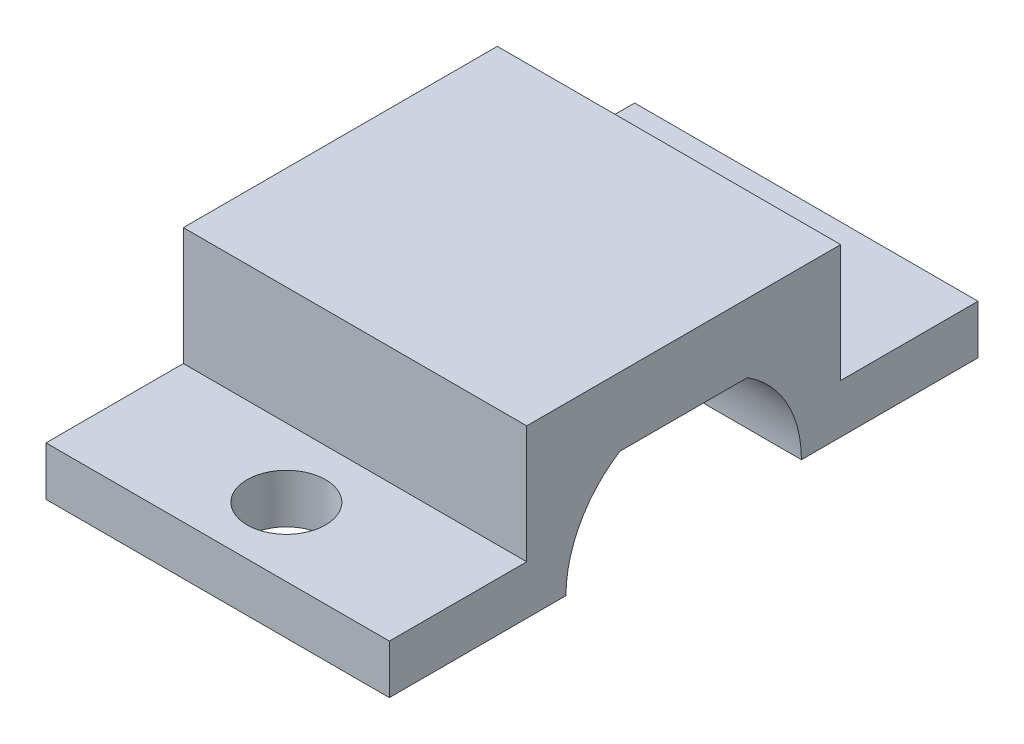
SolidWorks part; units mm, degrees
ref_plane "前基準面" through (0, 0, 0) normal (0, 0, 1) x (1, 0, 0)
ref_plane "上基準面" through (0, 0, 0) normal (0, 1, 0) x (1, 0, 0)
ref_plane "右基準面" through (0, 0, 0) normal (1, 0, 0) x (0, 0, -1)
sketch "草圖1" plane through (0, 0, 0) normal (1, 0, 0) x (0, 0, -1)
  line L0 (-3.25, 2.1203) -> (3.25, 2.1203)
  line L1 (-15, -2.8797) -> (-5.9998, -2.8797)
  line L2 (-15, -2.8797) -> (-15, -0.3829)
  line L3 (-8, 5.6171) -> (8, 5.6171)
  line L4 (15, -2.8797) -> (15, -0.3829)
  line L5 (6.0007, -2.8797) -> (15, -2.8797)
  line L6 (0, -1000) -> (0, 49000) construction
  line L7 (-15, -0.3829) -> (-8, -0.3829)
  line L8 (-8, -0.3829) -> (-8, 5.6171)
  line L13 (15, -0.3829) -> (8, -0.3829)
  line L14 (8, -0.3829) -> (8, 5.6171)
  arc A0 (-5.9998, -2.8797) -> (-3.25, 2.1203) centre (-0.0798, -2.8793) cw
  arc A1 (6.0007, -2.8797) -> (3.25, 2.1203) centre (0.0802, -2.8801) ccw
  dimension "D4" = 5.92
  dimension "D7" = 5.9205
  dimension "D1" = 5
  dimension "D2" = 6.5
  dimension "D3" = 0.16
  dimension "D5" = 7
  dimension "D6" = 6
extrude "填料-伸長1" add sketch "草圖1" along normal mid plane 17.5
sketch "草圖3" plane through (0, 0, 0) normal (0, 1, 0) x (1, 0, 0)
  line L0 (-1000, 0) -> (49000, 0) construction
  line L2 (8.75, 8) -> (-8.75, 8) construction
  circle A0 centre (0, 11.5) radius 2
  circle A1 centre (0, -11.5) radius 2
  dimension "D1" = 4
  dimension "D2" = 3.5
extrude "除料-伸長1" cut sketch "草圖3" against normal up to next
